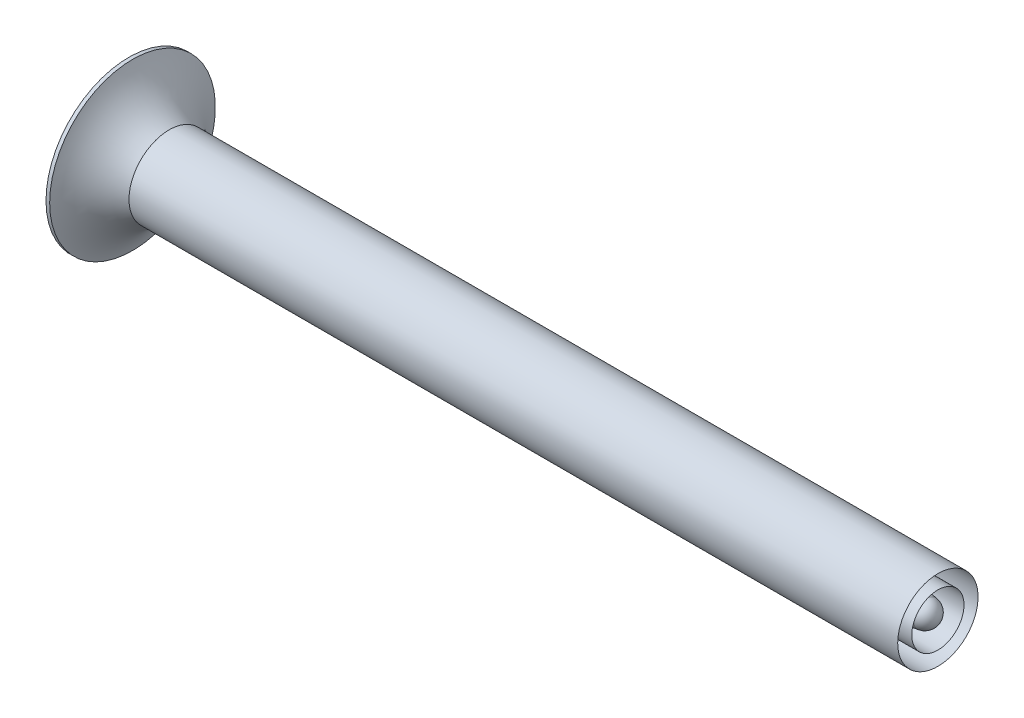
SolidWorks part; units mm, degrees
ref_plane "Front Plane" through (0, 0, 0) normal (0, 0, 1) x (1, 0, 0)
ref_plane "Top Plane" through (0, 0, 0) normal (0, 1, 0) x (1, 0, 0)
ref_plane "Right Plane" through (0, 0, 0) normal (1, 0, 0) x (0, 0, -1)
sketch "Sketch1" plane through (0, 0, 0) normal (0, 0, 1) x (1, 0, 0)
  line L0 (0, -4.0323) -> (0, 0)
  line L1 (0, 4.0322) -> (0.1778, 4.0322) construction
  line L2 (0.1778, 4.0322) -> (1.67, 2.54) construction
  line L3 (1.67, 2.54) -> (3.8608, 1.4605) construction
  line L4 (3.8608, 1.4605) -> (3.8608, -1.4605) construction
  line L5 (3.8608, -1.4605) -> (1.67, -2.54) construction
  line L6 (1.67, -2.54) -> (0.1778, -4.0323) construction
  line L7 (0.1778, -4.0323) -> (0, -4.0323)
  line L8 (0.1778, 4.0322) -> (0.1778, -4.0323) construction
  line L9 (1.67, 2.54) -> (1.67, -2.54) construction
  line L10 (0, 0) -> (38.735, 0) construction
  line L11 (3.8608, 1.4605) -> (32.5063, 1.4605) construction
  line L12 (3.8608, -1.4605) -> (16.51, -1.4605)
  line L13 (33.9533, -1.27) -> (38.8179, -0.6296)
  line L14 (38.8179, 0.6296) -> (32.5063, 1.4605) construction
  line L15 (32.5063, 1.4605) -> (32.5063, -1.4605) construction
  line L16 (38.8179, -0.6296) -> (43.5999, 0) construction
  line L17 (43.5999, 0) -> (38.8179, 0.6296) construction
  line L18 (0, 0) -> (39.37, 0)
  line L19 (0, 0) -> (0, 4.0322) construction
  line L20 (16.51, -1.4605) -> (17.957, -1.27)
  line L22 (17.957, -1.27) -> (33.9533, -1.27)
  line L23 (16.51, -1.4605) -> (32.5063, -1.4605) construction
  line L24 (32.5063, -1.4605) -> (33.9533, -1.27) construction
  line L25 (17.957, -1.27) -> (17.957, 1.27) construction
  arc A0 (39.37, 0) -> (38.8179, -0.6296) centre (38.735, 0) cw
  arc A1 (38.8179, 0.6296) -> (39.37, 0) centre (38.735, 0) cw construction
  arc A2 (3.8608, -1.4605) -> (0.1778, -4.0323) centre (3.8608, -5.3836) ccw
  point P3 (17.957, 0)
  point P14 (3.8608, 0)
  point P26 (3.8608, -4.2849)
  dimension "D10" = 0.635
  dimension "D1" = 8.0645
  dimension "D2" = 3.683
  dimension "D3" = 45
  dimension "D4" = 45
  dimension "D5" = 5.08
  dimension "D6" = 2.921
  dimension "D7" = 3.8608
  dimension "D8" = 39.37
  dimension "D9" = 15
  dimension "D11" = 7.5
  dimension "D12" = 2.54
  dimension "D13" = 22.86
revolve "Revolve1" add sketch "Sketch1" angle 360 about L18
sketch "Sketch2" plane through (0, 0, 0) normal (1, 0, 0) x (0, 0, -1)
  circle A1 centre (0, 0) radius 1.27
  circle A2 centre (0, 0) radius 1.27 construction
surface "Max Pre-Drill Diameter" sketch "Sketch2"
sketch "Sketch3" plane through (0, 0, 0) normal (-1, 0, 0) x (0, 0, 1)
  circle A0 centre (0, 0) radius 1.9558
  dimension "D1" = 3.9116
surface "Thread Diameter" sketch "Sketch3"
